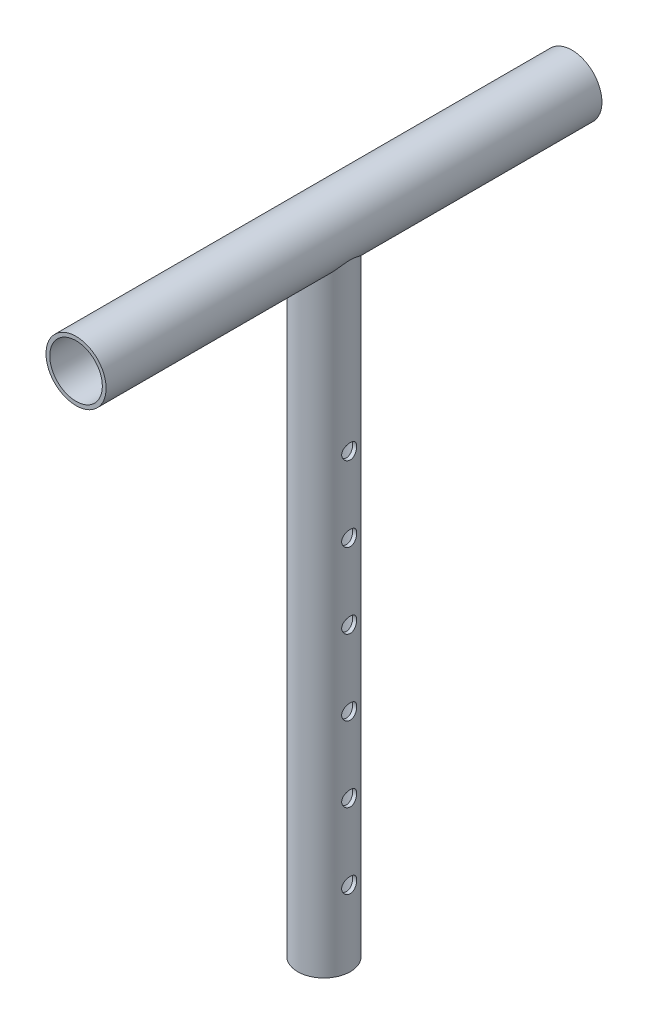
SolidWorks part; units mm, degrees
ref_plane "Front Plane" through (0, 0, 0) normal (0, 0, 1) x (1, 0, 0)
ref_plane "Top Plane" through (0, 0, 0) normal (0, 1, 0) x (1, 0, 0)
ref_plane "Right Plane" through (0, 0, 0) normal (1, 0, 0) x (0, 0, -1)
sketch "Sketch1" plane through (0, 0, 0) normal (0, 0, 1) x (1, 0, 0)
  circle A0 centre (0, 0) radius 20
  circle A1 centre (0, 0) radius 17.5
  dimension "D1" = 40
  dimension "D2" = 35
extrude "Boss-Extrude1" add sketch "Sketch1" along normal mid plane 330
sketch "Sketch2" plane through (0, 0, 0) normal (0, 0, 1) x (1, 0, 0)
  line L0 (0, -20) -> (0, -420)
  circle A0 centre (0, 0) radius 20 construction
  point P3 (0, -20)
  dimension "D1" = 400
ref_plane "Plane1" through (0, -420, 0) normal (0, 1, 0) x (1, 0, 0)
sketch "Sketch3" plane through (0, -420, 0) normal (0, 1, 0) x (1, 0, 0)
  circle A0 centre (0, 0) radius 17.5
  circle A1 centre (0, 0) radius 15
  dimension "D1" = 35
  dimension "D2" = 30
extrude "Boss-Extrude2" add sketch "Sketch3" along normal up to surface (400 mm away)
sketch "Sketch4" plane through (0, 0, 0) normal (0, 0, 1) x (1, 0, 0)
  line L0 (0, -20) -> (0, -420) construction
  point P0 (0, -370)
  point P6 (0, -320)
  point P7 (0, -270)
  point P8 (0, -220)
  point P9 (0, -170)
  point P10 (0, -120)
  dimension "D1" = 50
  dimension "D3" = 300
  dimension "D2" = 6
sketch "Sketch5" plane through (0, 0, 0) normal (1, 0, 0) x (0, 0, -1)
  circle A0 centre (0, -120) radius 5
  circle A1 centre (0, -170) radius 5
  circle A2 centre (0, -220) radius 5
  circle A3 centre (0, -270) radius 5
  circle A4 centre (0, -320) radius 5
  circle A5 centre (0, -370) radius 5
  point P0 (0, -370)
  point P2 (0, -320)
  point P4 (0, -270)
  point P6 (0, -220)
  point P8 (0, -170)
  point P10 (0, -120)
  dimension "D1" = 10
  dimension "D2" = 6
extrude "Cut-Extrude1" cut sketch "Sketch5" against normal through all both and the other way through all
sketch "Sketch6" plane through (0, 0, 0) normal (0, 0, 1) x (1, 0, 0)
  line L0 (0, 0) -> (0, -420)
  line L1 (17.5, -420) -> (-17.5, -420) construction
